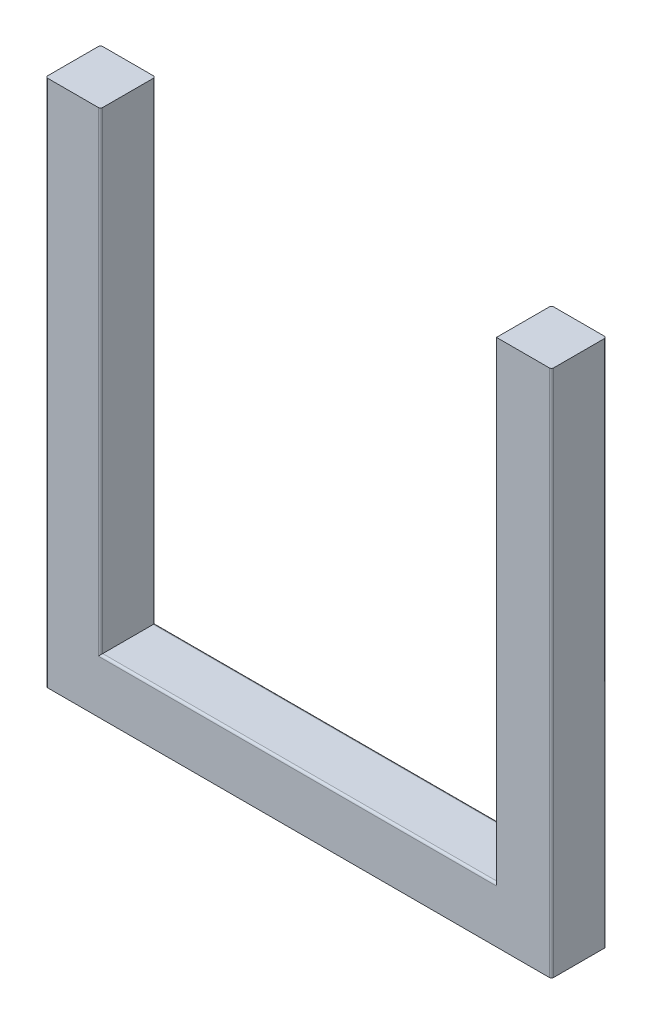
SolidWorks part; units mm, degrees
ref_plane "Front Plane" through (0, 0, 0) normal (0, 0, 1) x (1, 0, 0)
ref_plane "Top Plane" through (0, 0, 0) normal (0, 1, 0) x (1, 0, 0)
ref_plane "Right Plane" through (0, 0, 0) normal (1, 0, 0) x (0, 0, -1)
sketch "Sketch1" plane through (0, 0, 0) normal (0, 0, 1) x (1, 0, 0)
  line L0 (410, 50) -> (50, 50)
  line L1 (0, 0) -> (460, 0)
  line L2 (0, 0) -> (0, 50)
  line L4 (460, 0) -> (460, 50)
  line L6 (460, 50) -> (460, 480)
  line L7 (460, 480) -> (410, 480)
  line L8 (410, 50) -> (410, 480)
  line L9 (0, 0) -> (0, 480)
  line L10 (0, 480) -> (50, 480)
  line L11 (50, 480) -> (50, 50)
  dimension "D1" = 460
  dimension "D2" = 480
  dimension "D3" = 50
  dimension "D4" = 50
extrude "Boss-Extrude1" add sketch "Sketch1" along normal blind 50
fillet "Fillet1" radius 2 10 edges at (230, 50, 0) (230, 50, 50) (50, 265, 0) (50, 265, 50) (0, 240, 0) (0, 240, 50) (460, 240, 0) (460, 240, 50) (230, 0, 0) (410, 265, 0)
